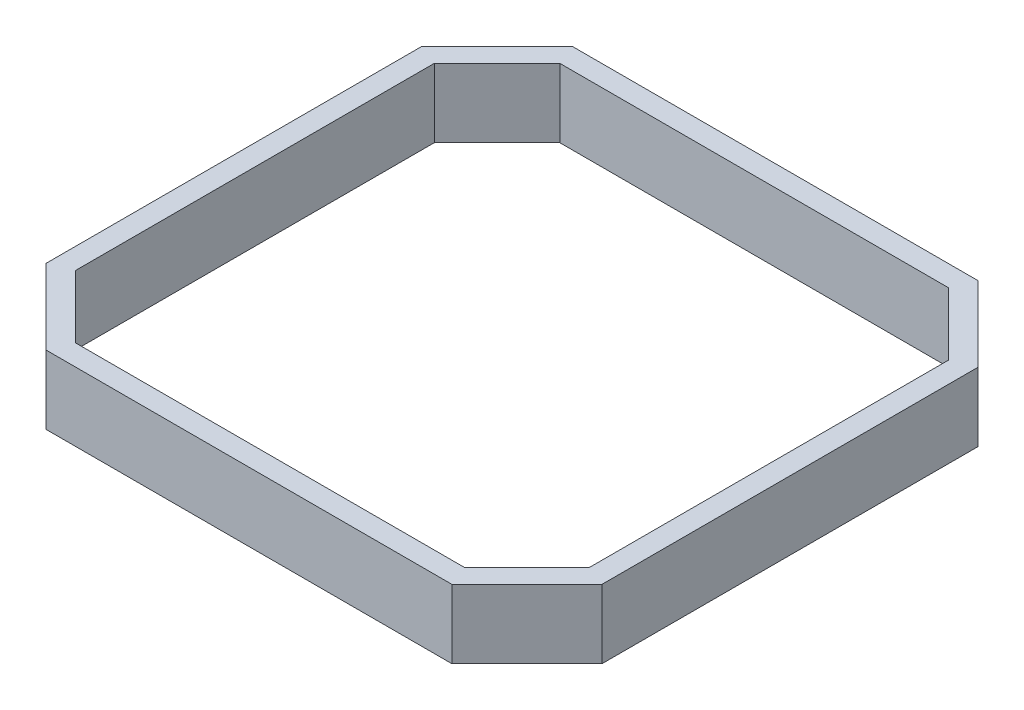
SolidWorks part; units mm, degrees
material "Copper"
ref_plane "Front Plane" through (0, 0, 0) normal (0, 0, 1) x (1, 0, 0)
ref_plane "Top Plane" through (0, 0, 0) normal (0, 1, 0) x (1, 0, 0)
ref_plane "Right Plane" through (0, 0, 0) normal (1, 0, 0) x (0, 0, -1)
sketch "Sketch1" plane through (0, 0, 0) normal (0, 1, 0) x (1, 0, 0)
  line L0 (-43, 30) -> (-32.5, 40.5)
  line L1 (-32.5, -40.5) -> (32.5, -40.5)
  line L2 (-43, -30) -> (-43, 30)
  line L3 (-32.5, 40.5) -> (32.5, 40.5)
  line L4 (43, -30) -> (43, 30)
  line L5 (0, 0) -> (0, -40.5) construction
  line L6 (0, 0) -> (-43, 0) construction
  line L7 (-43, -30) -> (-32.5, -40.5)
  line L8 (32.5, -40.5) -> (43, -30)
  line L9 (32.5, 40.5) -> (43, 30)
  line L10 (0, 0) -> (0, 40.5) construction
  line L11 (0, 0) -> (43, 0) construction
  line L12 (-46.5, 31.4497) -> (-33.9497, 44)
  line L13 (-33.9497, 44) -> (33.9497, 44)
  line L14 (33.9497, 44) -> (46.5, 31.4497)
  line L15 (46.5, -31.4497) -> (46.5, 31.4497)
  line L16 (33.9497, -44) -> (46.5, -31.4497)
  line L17 (-33.9497, -44) -> (33.9497, -44)
  line L18 (-46.5, -31.4497) -> (-33.9497, -44)
  line L19 (-46.5, -31.4497) -> (-46.5, 31.4497)
  point P0 (0, 0)
  point P1 (0, 0)
  point P15 (0, 0)
  point P17 (-40.4917, 30)
  point P18 (-42.8208, 0)
  point P19 (37.7525, 22.3163)
  dimension "D1" = 86
  dimension "D2" = 81
  dimension "D3" = 60
  dimension "D4" = 65
  dimension "D5" = 3.5
extrude "Boss-Extrude1" add sketch "Sketch1" along normal blind 11.5
